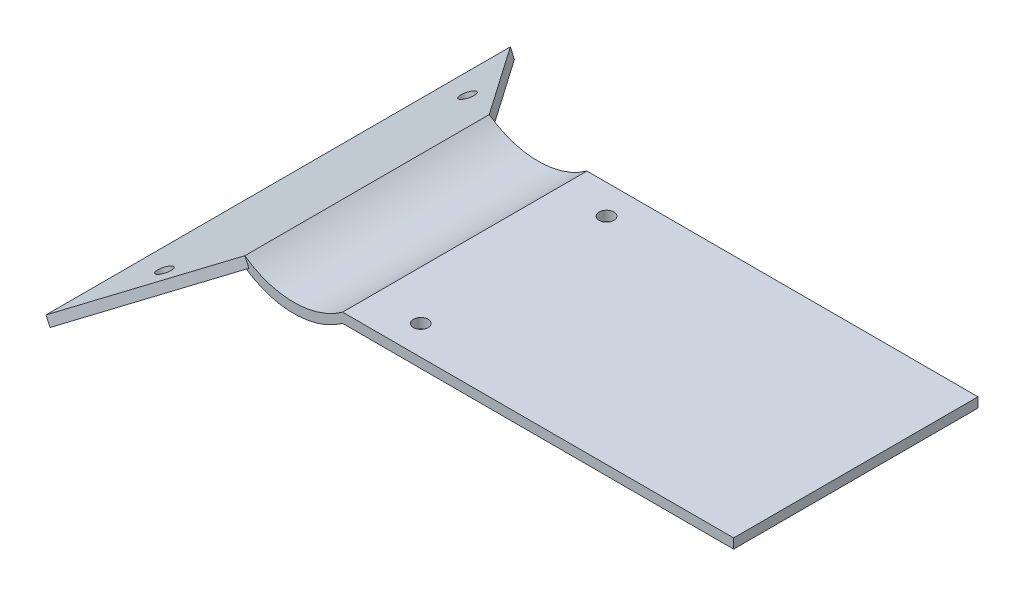
SolidWorks part; units mm, degrees
material "PBT 一般用途"
ref_plane "前视基准面" through (0, 0, 0) normal (0, 0, 1) x (1, 0, 0)
ref_plane "上视基准面" through (0, 0, 0) normal (0, 1, 0) x (1, 0, 0)
ref_plane "右视基准面" through (0, 0, 0) normal (1, 0, 0) x (0, 0, -1)
sketch "草图1" plane through (0, 0, 0) normal (0, 0, 1) x (1, 0, 0)
  line L0 (-600, 10) -> (-600, -10)
  line L1 (400, -10) -> (-400, -10)
  line L2 (400, -10) -> (400, 10)
  line L3 (400, 10) -> (-400, 10)
  line L4 (-400, -10) -> (-400, 10)
  line L5 (400, -10) -> (-400, 10) construction
  line L6 (400, 10) -> (-400, -10) construction
  line L7 (-600, -10) -> (-818.1742, -110)
  line L8 (-600, 10) -> (-781.8119, -73.3333)
  line L9 (-781.8119, -73.3333) -> (-818.1742, -110)
  arc A0 (-600, -10) -> (-400, -10) centre (-500, 127.4773) ccw
  arc A1 (-600, 10) -> (-400, 10) centre (-500, 147.4773) ccw
  point P0 (0, 0)
  dimension "D3" = 170
  dimension "D4" = 170
  dimension "D1" = 800
  dimension "D2" = 20
  dimension "D5" = 200
  dimension "D6" = 200
  dimension "D7" = 240
  dimension "D8" = 100
extrude "凸台-拉伸1" add sketch "草图1" along normal blind 500 contours L4 L1 L2 L3 | A1 L0 A0 L4 | L8 L9 L7 L0
sketch "草图3" plane through (-107.9544, 235.5287, 0) normal (-0.4167, 0.9091, 0) x (0.9091, 0.4167, 0)
  line L0 (-541.2689, 0) -> (-741.2689, 225)
  line L1 (-741.2689, 225) -> (-741.2689, 0)
  line L2 (-541.2689, -250) -> (-741.2689, -250) construction
  line L3 (-541.2689, -500) -> (-541.2689, 0) construction
  line L4 (-741.2689, -500) -> (-741.2689, 0) construction
  line L5 (-741.2689, -725) -> (-741.2689, -500)
  line L6 (-541.2689, -500) -> (-741.2689, -725)
  line L7 (-541.2689, 0) -> (-741.2689, 0) construction
  circle A0 centre (-656.2689, 60) radius 15
  circle A1 centre (-656.2689, -560) radius 15
  line M1 (-541.2689, 0) -> (-741.2689, 0)
  line M3 (-741.2689, -500) -> (-541.2689, -500)
  dimension "D1" = 85
  dimension "D5" = 30
  dimension "D2" = 60
  dimension "D3" = 225
extrude "凸台-拉伸2" add sketch "草图3" against normal blind 20 contours L6 L5 M3 | L0 L1 M1
sketch "草图5" plane through (0, 10, 0) normal (0, 1, 0) x (1, 0, 0)
  line L0 (-400, -250) -> (-286.9738, -250) construction
  line L3 (-400, -500) -> (-400, 0) construction
  line L4 (400, 0) -> (-400, 0) construction
  circle A0 centre (-300, -60) radius 15
  circle A1 centre (-300, -440) radius 15
  circle A2 centre (-300, -440) radius 15
  dimension "D1" = 100
  dimension "D3" = 30
  dimension "D2" = 60
extrude "切除-拉伸2" cut sketch "草图5" against normal through all contours A1 | A0
